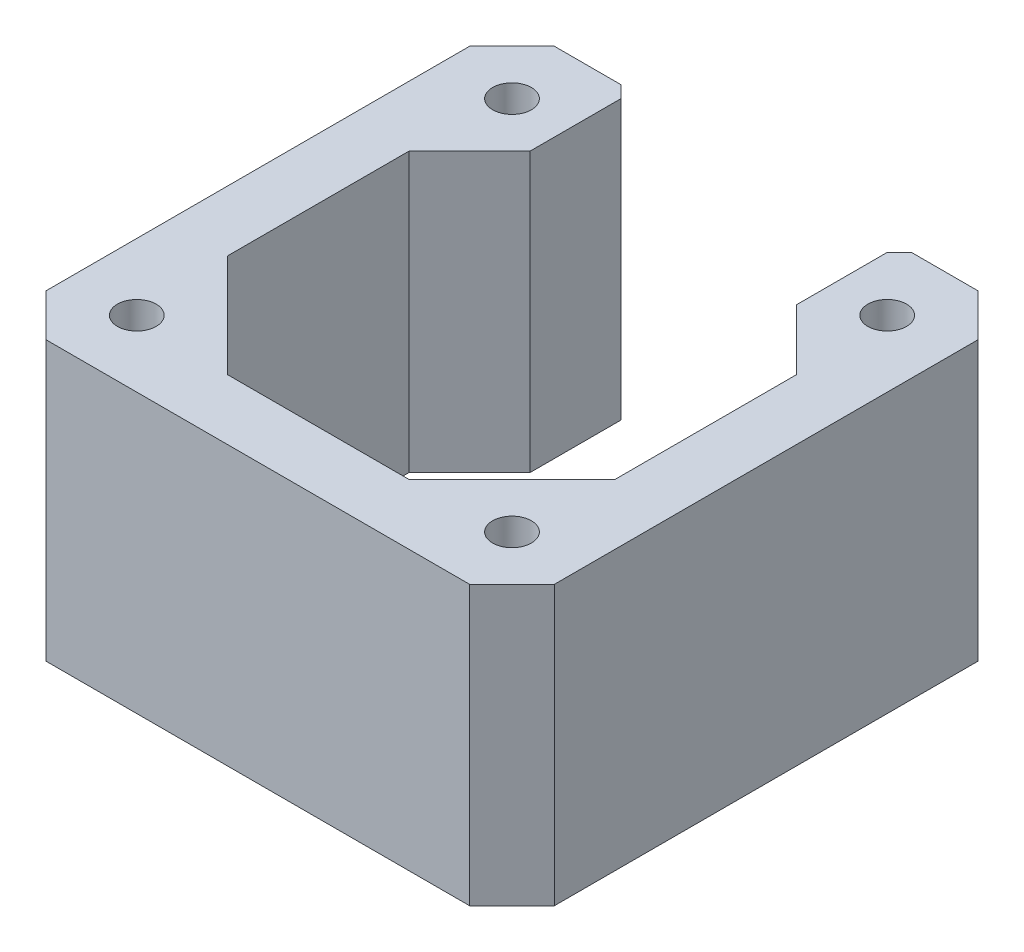
SolidWorks part; units mm, degrees
material "PLA+"
ref_plane "Спереди" through (0, 0, 0) normal (0, 0, 1) x (1, 0, 0)
ref_plane "Сверху" through (0, 0, 0) normal (0, 1, 0) x (1, 0, 0)
ref_plane "Справа" through (0, 0, 0) normal (1, 0, 0) x (0, 0, -1)
sketch "Sketch1" plane through (0, 0, 0) normal (0, 1, 0) x (1, 0, 0)
  line L0 (-16, -7.5) -> (-7.5, -16)
  line L1 (-7.5, -16) -> (7.5, -16)
  line L2 (-17.5, 21) -> (-21, 17.5)
  line L3 (-21, 17.5) -> (-21, -17.5)
  line L4 (-21, -17.5) -> (-17.5, -21)
  line L5 (-17.5, -21) -> (17.5, -21)
  line L6 (21, -17.5) -> (17.5, -21)
  line L7 (16, -7.5) -> (7.5, -16)
  line L8 (16, 7.5) -> (16, -7.5)
  line L9 (-17.5, 21) -> (-12, 21)
  line L10 (-16, 7.5) -> (-16, -7.5)
  line L11 (0, 0) -> (0, 30.1714) construction
  line L12 (-11, 20) -> (-11, 12.5)
  line L13 (-11, 12.5) -> (-16, 7.5)
  line L14 (21, 17.5) -> (21, -17.5)
  line L15 (17.5, 21) -> (21, 17.5)
  line L16 (17.5, 21) -> (12, 21)
  line L17 (11, 20) -> (11, 12.5)
  line L18 (11, 12.5) -> (16, 7.5)
  line L19 (-12, 21) -> (-11, 20)
  line L20 (12, 21) -> (11, 20)
  circle A0 centre (-15.5, 15.5) radius 1.6
  circle A1 centre (-15.5, -15.5) radius 1.6
  circle A2 centre (15.5, -15.5) radius 1.6
  circle A3 centre (15.5, 15.5) radius 1.6
  point P0 (-11, 21)
  point P37 (11, 21)
  dimension "D13" = 3.2
  dimension "D20" = 3.2
  dimension "D3" = 35
  dimension "D4" = 5
  dimension "D5" = 3.5
  dimension "D6" = 35
  dimension "D7" = 16
  dimension "D8" = 6.5
  dimension "D9" = 8.5
  dimension "D10" = 3.5
  dimension "D11" = 3.5
  dimension "D12" = 5
  dimension "D14" = 15.5
  dimension "D15" = 15.5
  dimension "D16" = 15
  dimension "D17" = 7.5
  dimension "D18" = 15.5
  dimension "D19" = 15.5
extrude "Base" add sketch "Sketch1" along normal blind 23 and the other way blind 0.0001
